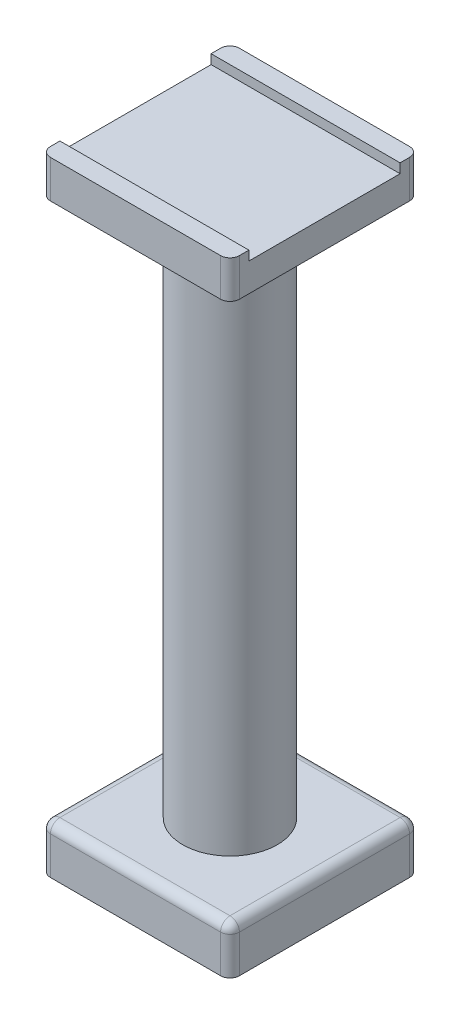
SolidWorks part; units mm, degrees
ref_plane "前视基准面" through (0, 0, 0) normal (0, 0, 1) x (1, 0, 0)
ref_plane "上视基准面" through (0, 0, 0) normal (0, 1, 0) x (1, 0, 0)
ref_plane "右视基准面" through (0, 0, 0) normal (1, 0, 0) x (0, 0, -1)
other "Configuration Table"
sketch "草图1" plane through (0, 0, 0) normal (0, 1, 0) x (1, 0, 0)
  line L1 (0, 0) -> (-20, 0)
  line L2 (0, 0) -> (0, 20)
  line L3 (0, 20) -> (-20, 20)
  line L4 (-20, 0) -> (-20, 20)
  dimension "D1" = 20
  dimension "D2" = 20
extrude "凸台-拉伸1" add sketch "草图1" along normal blind 5
sketch "草图2" plane through (0, 5, 0) normal (0, 1, 0) x (1, 0, 0)
  circle A0 centre (-10, 10) radius 5
extrude "凸台-拉伸2" add sketch "草图2" along normal blind 57
sketch "草图4" plane through (0, 62, 0) normal (0, 1, 0) x (1, 0, 0)
  line L2 (-20, 20) -> (0, 20)
  line L3 (-20, 20) -> (-20, 0)
  line L4 (-20, 0) -> (0, 0)
  line L5 (0, 20) -> (0, 0)
extrude "凸台-拉伸3" add sketch "草图4" along normal blind 3
sketch "草图5" plane through (0, 65, 0) normal (0, 1, 0) x (1, 0, 0)
  line L1 (-20, 0) -> (-20, 2)
  line L2 (-20, 20) -> (-20, 0) construction
  line L4 (-20, 20) -> (0, 20)
  line L5 (-20, 2) -> (0, 2)
  line L6 (-20, 2) -> (-20, 0)
  line L7 (-20, 0) -> (0, 0)
  line L8 (0, 2) -> (0, 0)
  line L9 (0, 18) -> (0, 20)
  line L10 (-20, 18) -> (0, 18)
  line L11 (-20, 18) -> (-20, 20)
  dimension "D1" = 2
extrude "凸台-拉伸4" add sketch "草图5" along normal blind 1 contours L10 L9 L4 L11
sketch "草图6" plane through (0, 65, 0) normal (0, 1, 0) x (1, 0, 0)
  line L0 (0, 0) -> (0, 18) construction
  line L1 (-20, 0) -> (0, 0)
  line L2 (-20, 0) -> (-20, 2)
  line L3 (-20, 2) -> (0, 2)
  line L4 (0, 0) -> (0, 2)
  dimension "D1" = 2
extrude "凸台-拉伸5" add sketch "草图6" along normal blind 1
fillet "圆角1" radius 1 1 edges at (0, 64, 0)
fillet "圆角2" radius 1 3 edges at (-20, 64, -20) (-20, 64, 0) (0, 64, -20)
fillet "圆角3" radius 1 8 edges at (-20, 2.5, -20) (-20, 2.5, 0) (0, 2.5, 0) (0, 2.5, -20) (-10, 5, -20) (0, 5, -10) (-20, 5, -10) (-10, 5, 0)
